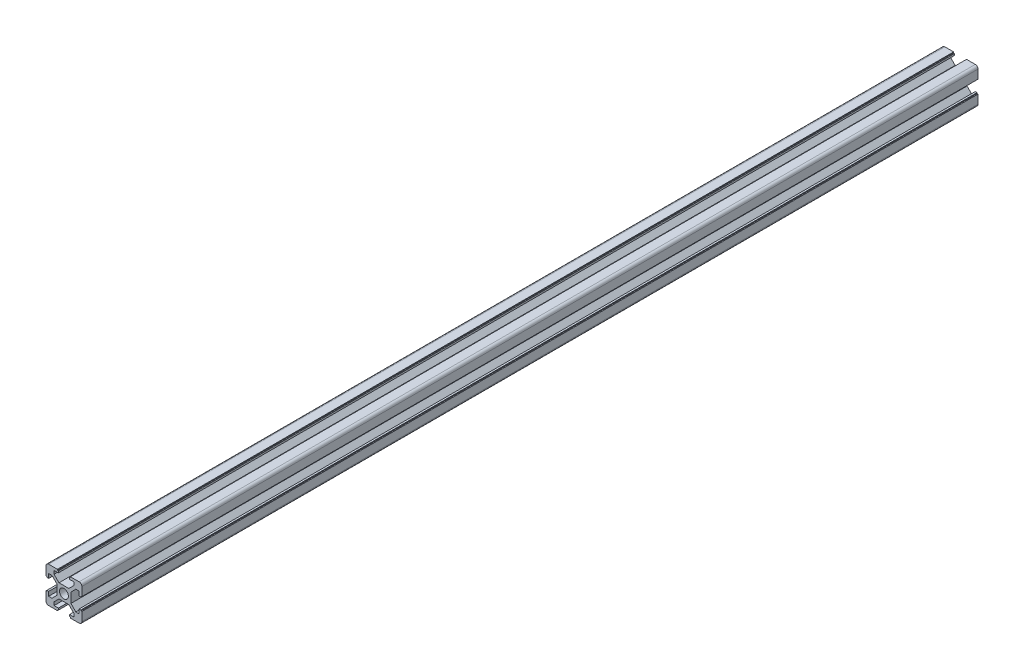
SolidWorks part; units mm, degrees
ref_plane "前视基准面" through (0, 0, 0) normal (0, 0, 1) x (1, 0, 0)
ref_plane "上视基准面" through (0, 0, 0) normal (0, 1, 0) x (1, 0, 0)
ref_plane "右视基准面" through (0, 0, 0) normal (1, 0, 0) x (0, 0, -1)
other "Configuration Table"
sketch "草图1" plane through (0, 0, 0) normal (1, 0, 0) x (0, 0, -1)
  line L0 (0, 0) -> (500, 0)
  dimension "D1" = 500
other "铝型材 20 X 20 X R1.5(1)"
ref_plane "基准面1" through (0, 0, 0) normal (0, 0, -1) x (0, 1, 0)
sketch "Sketch13" plane through (0, 0, 0) normal (0, 0, -1) x (0, 1, 0)
  line L0 (-3.6, 10) -> (-3.6, 9.5)
  line L1 (-3.6, 9.5) -> (-3.1, 9.5)
  line L2 (-3.1, 9.5) -> (-3.1, 8.5)
  line L3 (-3.1, 8.5) -> (-5.5, 8.5)
  line L4 (-8.5, -10) -> (-3.6, -10)
  line L5 (-10, -8.5) -> (-10, -3.6)
  line L6 (8.5, 10) -> (3.6, 10)
  line L7 (10, 8.5) -> (10, 3.6)
  line L8 (0, 14.8756) -> (0, 0) construction
  line L9 (0, 0) -> (14.1675, 0) construction
  line L10 (-5.5, 8.5) -> (-5.5, 6.65)
  line L11 (-5.5, 6.65) -> (-2.75, 3.9)
  line L12 (-2.75, 3.9) -> (2.75, 3.9)
  line L13 (5.5, 6.65) -> (2.75, 3.9)
  line L14 (5.5, 8.5) -> (5.5, 6.65)
  line L15 (3.1, 8.5) -> (5.5, 8.5)
  line L16 (3.1, 9.5) -> (3.1, 8.5)
  line L17 (3.6, 9.5) -> (3.1, 9.5)
  line L18 (3.6, 10) -> (3.6, 9.5)
  line L19 (-3.6, 10) -> (-8.5, 10)
  line L20 (10, 3.6) -> (9.5, 3.6)
  line L21 (9.5, 3.6) -> (9.5, 3.1)
  line L22 (9.5, 3.1) -> (8.5, 3.1)
  line L23 (8.5, 3.1) -> (8.5, 5.5)
  line L24 (8.5, 5.5) -> (6.65, 5.5)
  line L25 (6.65, 5.5) -> (3.9, 2.75)
  line L26 (3.9, 2.75) -> (3.9, -2.75)
  line L27 (6.65, -5.5) -> (3.9, -2.75)
  line L28 (8.5, -5.5) -> (6.65, -5.5)
  line L29 (8.5, -3.1) -> (8.5, -5.5)
  line L30 (9.5, -3.1) -> (8.5, -3.1)
  line L31 (9.5, -3.6) -> (9.5, -3.1)
  line L32 (10, -3.6) -> (9.5, -3.6)
  line L33 (3.6, -10) -> (3.6, -9.5)
  line L34 (3.6, -9.5) -> (3.1, -9.5)
  line L35 (3.1, -9.5) -> (3.1, -8.5)
  line L36 (3.1, -8.5) -> (5.5, -8.5)
  line L37 (5.5, -8.5) -> (5.5, -6.65)
  line L38 (5.5, -6.65) -> (2.75, -3.9)
  line L39 (2.75, -3.9) -> (-2.75, -3.9)
  line L40 (-5.5, -6.65) -> (-2.75, -3.9)
  line L41 (-5.5, -8.5) -> (-5.5, -6.65)
  line L42 (-3.1, -8.5) -> (-5.5, -8.5)
  line L43 (-3.1, -9.5) -> (-3.1, -8.5)
  line L44 (-3.6, -9.5) -> (-3.1, -9.5)
  line L45 (-3.6, -10) -> (-3.6, -9.5)
  line L46 (-10, -3.6) -> (-9.5, -3.6)
  line L47 (-9.5, -3.6) -> (-9.5, -3.1)
  line L48 (-9.5, -3.1) -> (-8.5, -3.1)
  line L49 (-8.5, -3.1) -> (-8.5, -5.5)
  line L50 (-8.5, -5.5) -> (-6.65, -5.5)
  line L51 (-6.65, -5.5) -> (-3.9, -2.75)
  line L52 (-3.9, -2.75) -> (-3.9, 2.75)
  line L53 (-6.65, 5.5) -> (-3.9, 2.75)
  line L54 (-8.5, 5.5) -> (-6.65, 5.5)
  line L55 (-8.5, 3.1) -> (-8.5, 5.5)
  line L56 (-9.5, 3.1) -> (-8.5, 3.1)
  line L57 (-9.5, 3.6) -> (-9.5, 3.1)
  line L58 (-10, 3.6) -> (-9.5, 3.6)
  line L59 (3.6, -10) -> (8.5, -10)
  line L60 (-10, 3.6) -> (-10, 8.5)
  line L61 (10, -3.6) -> (10, -8.5)
  circle A0 centre (0, 0) radius 2.5
  arc A1 (-10, 8.5) -> (-8.5, 10) centre (-8.5, 8.5) cw
  arc A2 (10, 8.5) -> (8.5, 10) centre (8.5, 8.5) ccw
  arc A3 (-8.5, -10) -> (-10, -8.5) centre (-8.5, -8.5) cw
  arc A4 (8.5, -10) -> (10, -8.5) centre (8.5, -8.5) ccw
  point P0 (-10, 0)
  point P1 (10, 0)
  point P2 (0, 10)
  point P3 (0, -10)
  point P4 (0, 0)
  point P5 (-10, -10)
  point P6 (10, -10)
  point P7 (10, 10)
  point P8 (-10, 10)
  point P13 (0, 0)
  point P36 (-10, 10)
  point P39 (10, 10)
  dimension "D1" = 11
  dimension "D2" = 20
  dimension "D3" = 6.2
  dimension "D4" = 7.2
  dimension "D5" = 6.1
  dimension "D6" = 5
  dimension "D7" = 1.5
  dimension "D8" = 45
  dimension "D9" = 0.5
  dimension "D10" = 1
  dimension "D11" = 5.5
